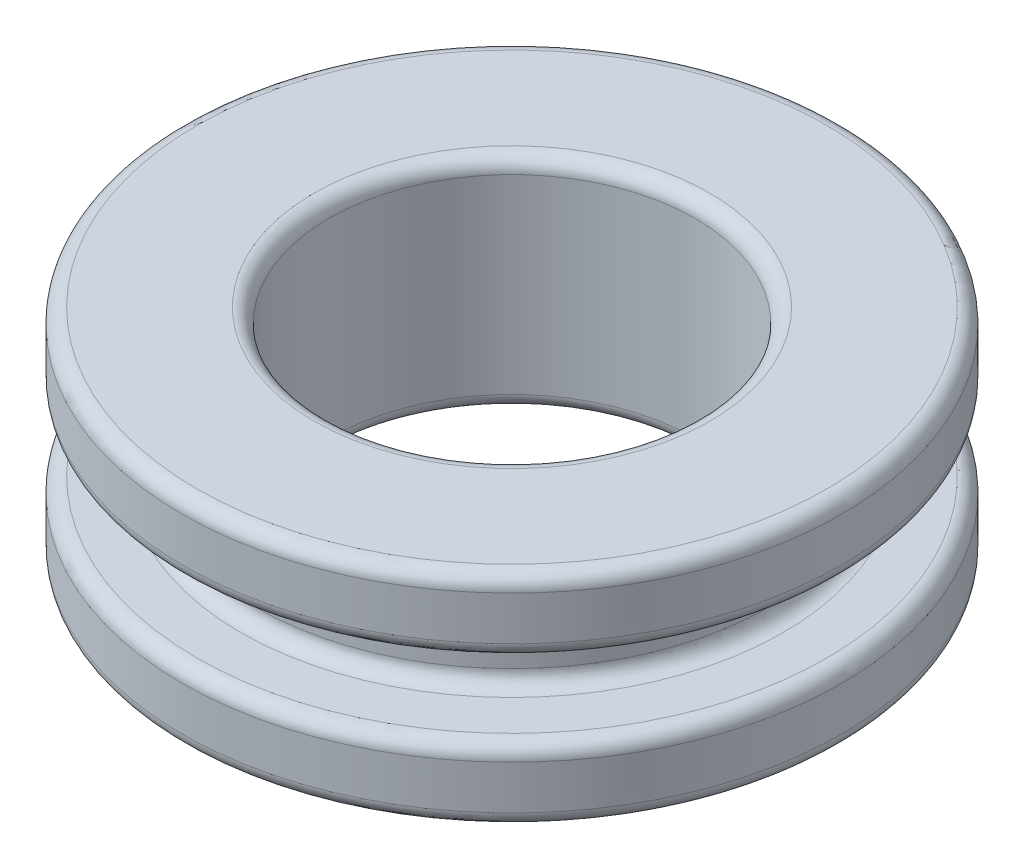
SolidWorks part; units mm, degrees
material "Rubber"
ref_plane "Front" through (0, 0, 0) normal (0, 0, 1) x (1, 0, 0)
ref_plane "Top" through (0, 0, 0) normal (0, 1, 0) x (1, 0, 0)
ref_plane "Right" through (0, 0, 0) normal (1, 0, 0) x (0, 0, -1)
sketch "Sketch1" plane through (0, 0, 0) normal (0, 0, 1) x (1, 0, 0)
  line L0 (0, 0) -> (0, 9.525) construction
  line L1 (7.9375, 0) -> (14.2875, 0)
  line L2 (7.9375, 0) -> (7.9375, 9.525)
  line L3 (7.9375, 9.525) -> (14.2875, 9.525)
  line L4 (14.2875, 0) -> (14.2875, 3.175)
  line L5 (0, 9.525) -> (7.9375, 9.525) construction
  line L6 (0, 0) -> (7.9375, 0) construction
  line L7 (14.2875, 6.35) -> (11.1125, 6.35)
  line L8 (11.1125, 6.35) -> (11.1125, 3.175)
  line L9 (11.1125, 3.175) -> (14.2875, 3.175)
  line L10 (14.2875, 6.35) -> (14.2875, 9.525)
  dimension "D1" = 9.525
  dimension "D2" = 28.575
  dimension "D3" = 15.875
  dimension "D4" = 3.175
  dimension "D5" = 22.225
revolve "Revolve1" add sketch "Sketch1" angle 360 about L0
fillet "Fillet2" radius 0.635 8 edges at (0, 0, -14.2875) (0, 3.175, -14.2875) (0, 6.35, -14.2875) (0, 9.525, -14.2875) (0, 9.525, -7.9375) (0, 0, -7.9375) (0, 3.175, -11.1125) (0, 6.35, -11.1125)
